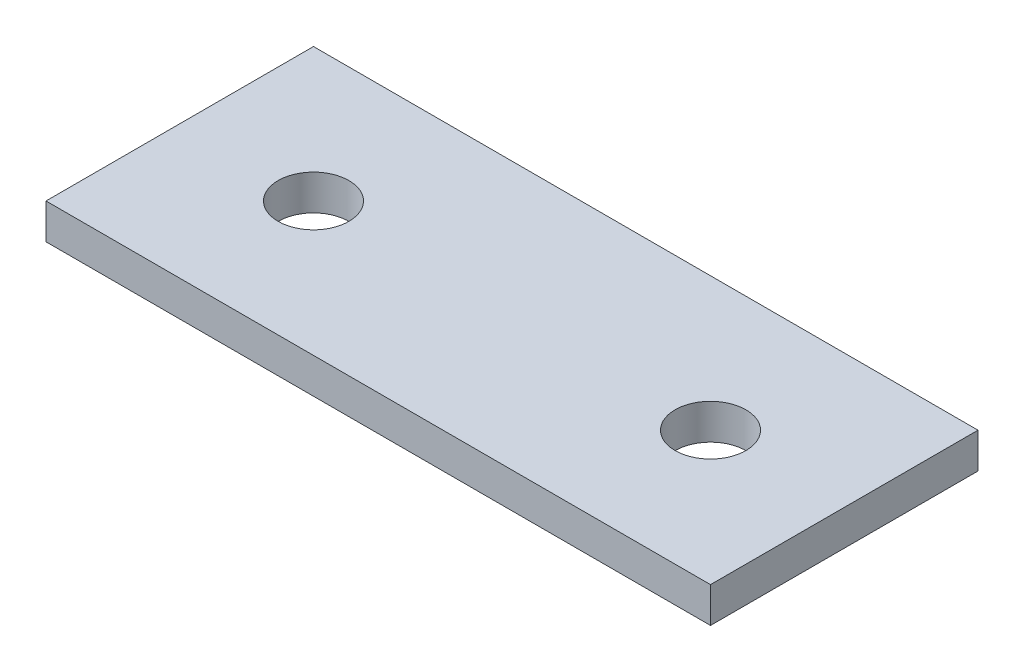
SolidWorks part; units mm, degrees
ref_plane "Front Plane" through (0, 0, 0) normal (0, 0, 1) x (1, 0, 0)
ref_plane "Top Plane" through (0, 0, 0) normal (0, 1, 0) x (1, 0, 0)
ref_plane "Right Plane" through (0, 0, 0) normal (1, 0, 0) x (0, 0, -1)
sketch "Sketch1" plane through (0, 0, 0) normal (0, 1, 0) x (1, 0, 0)
  line L0 (-8.905, 0) -> (8.905, 0) construction
  line L1 (14.905, -6) -> (-14.905, -6)
  line L2 (14.905, -6) -> (14.905, 6)
  line L3 (14.905, 6) -> (-14.905, 6)
  line L4 (-14.905, -6) -> (-14.905, 6)
  line L5 (14.905, -6) -> (-14.905, 6) construction
  line L6 (14.905, 6) -> (-14.905, -6) construction
  circle A0 centre (-8.905, 0) radius 1.5875
  circle A1 centre (8.905, 0) radius 1.5875
  circle A2 centre (-8.905, 0) radius 5 construction
  point P0 (0, 0)
  point P8 (0, 0)
  dimension "D1" = 3.175
  dimension "D4" = 10
  dimension "D2" = 17.81
  dimension "D3" = 12
  dimension "D5" = 6
extrude "Boss-Extrude1" add sketch "Sketch1" along normal mid plane 1.5875
sketch "Sketch2" plane through (0, -0.7937, 0) normal (0, -1, 0) x (1, 0, 0)
  line L0 (8.905, 0) -> (-8.905, 0) construction
